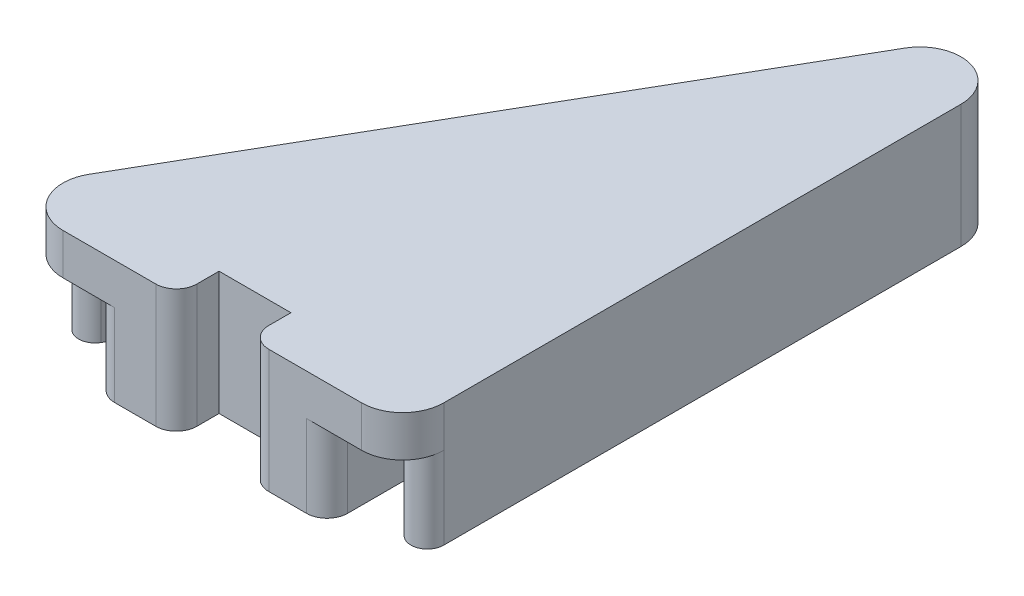
SolidWorks part; units mm, degrees
material "Pine"
ref_plane "Front Plane" through (0, 0, 0) normal (0, 0, 1) x (1, 0, 0)
ref_plane "Top Plane" through (0, 0, 0) normal (0, 1, 0) x (1, 0, 0)
ref_plane "Right Plane" through (0, 0, 0) normal (1, 0, 0) x (0, 0, -1)
sketch "Sketch1" plane through (0, 0, 0) normal (0, 1, 0) x (1, 0, 0)
  line L10 (0, 6.35) -> (0, 86.2867)
  line L11 (-11.8493, 89.4617) -> (-58.0007, 9.525)
  line L12 (-52.5015, 0) -> (-6.35, 0)
  arc A6 (-58.0007, 9.525) -> (-52.5015, 0) centre (-52.5015, 6.35) ccw
  arc A7 (0, 6.35) -> (-6.35, 0) centre (-6.35, 6.35) cw
  arc A8 (0, 86.2867) -> (-11.8493, 89.4617) centre (-6.35, 86.2867) ccw
  point P3 (-63.5, 0)
  point P4 (0, 0)
  point P7 (0, 0)
  point P10 (0, 0)
  point P13 (0, 109.9852)
  dimension "D2" = 6.35
  dimension "D1" = 63.5
  dimension "D3" = 60
extrude "Boss-Extrude1" add sketch "Sketch1" along normal blind 19.05
sketch "Sketch2" plane through (0, 19.05, 0) normal (0, 1, 0) x (1, 0, 0)
  line L0 (-52.5015, 0) -> (-6.35, 0) construction
  line L1 (-34.982, 0) -> (-23.8695, 0)
  line L2 (-34.982, 0) -> (-34.982, 6.604)
  line L3 (-34.982, 6.604) -> (-23.8695, 6.604)
  line L4 (-23.8695, 0) -> (-23.8695, 6.604)
  line L7 (0, 6.35) -> (0, 86.2867) construction
  dimension "D1" = 11.1125
  dimension "D2" = 6.604
  dimension "D3" = 23.8695
extrude "Cut-Extrude1" cut sketch "Sketch2" against normal through all
sketch "Sketch3" plane through (0, 0, 0) normal (0, 1, 0) x (1, 0, 0)
  line L0 (-22.1513, 48.2501) -> (-50.0085, 0)
  line L1 (-11.684, 45.4454) -> (-11.684, 0)
  line L2 (-11.8493, 89.4617) -> (-58.0007, 9.525) construction
  line L3 (-11.8493, 89.4617) -> (-58.0007, 9.525) construction
  line L4 (0, 86.2867) -> (0, 6.35) construction
  line L5 (0, 6.35) -> (0, 86.2867) construction
  line L7 (-5.08, 6.35) -> (-5.08, 36.8389)
  line L8 (-32.1738, 44.0986) -> (-53.6013, 6.985)
  line L9 (-41.7991, 27.427) -> (-46.1985, 29.967) construction
  line L11 (-41.7991, 27.427) -> (-36.0799, 24.125) construction
  line L12 (-5.08, 21.5944) -> (0, 21.5944) construction
  line L14 (-50.0085, 0) -> (-52.5015, 0)
  line L15 (-6.35, 0) -> (-11.684, 0)
  line L16 (-52.5015, 0) -> (-34.982, 0) construction
  line L17 (-23.8695, 0) -> (-6.35, 0) construction
  line L18 (-32.1738, 44.0986) -> (-27.8705, 51.5521)
  line L19 (-5.08, 45.4454) -> (-5.08, 36.8389)
  arc A0 (-22.1513, 48.2501) -> (-11.684, 45.4454) centre (-17.2934, 45.4454) cw
  arc A3 (-11.8493, 89.4617) -> (0, 86.2867) centre (-6.35, 86.2867) cw construction
  arc A4 (0, 86.2867) -> (-11.8493, 89.4617) centre (-6.35, 86.2867) ccw construction
  arc A7 (-5.08, 45.4454) -> (-27.8705, 51.5521) centre (-17.2934, 45.4454) ccw
  arc A10 (-53.6013, 6.985) -> (-58.0007, 9.525) centre (-55.801, 8.255) cw
  arc A11 (-58.0007, 9.525) -> (-52.5015, 0) centre (-52.5015, 6.35) ccw construction
  arc A12 (-5.08, 6.35) -> (0, 6.35) centre (-2.54, 6.35) ccw
  arc A13 (-6.35, 0) -> (0, 6.35) centre (-6.35, 6.35) ccw construction
  arc A14 (-32.1738, 44.0986) -> (-15.8416, 50.8636) centre (-19.5995, 36.8389) cw construction
  arc A15 (-15.8416, 50.8636) -> (-5.08, 36.8389) centre (-19.5995, 36.8389) cw construction
  arc A16 (-52.5015, 0) -> (-58.0007, 9.525) centre (-52.5015, 6.35) cw
  arc A17 (-6.35, 0) -> (0, 6.35) centre (-6.35, 6.35) ccw
  arc A18 (-6.35, 0) -> (0, 6.35) centre (-6.35, 6.35) ccw construction
  arc A19 (-58.0007, 9.525) -> (-52.5015, 0) centre (-52.5015, 6.35) ccw construction
  dimension "D2" = 5.08
  dimension "D3" = 316.1792
  dimension "D1" = 6.604
extrude "Cut-Extrude2" cut sketch "Sketch3" along normal blind 12.7
fillet "Fillet1" radius 3.175 4 edges at (-11.684, 6.35, 0) (-23.8695, 9.525, 0) (-34.982, 9.525, 0) (-50.0085, 6.35, 0)
ref_plane "Plane1" through (0, 0, -21.5944) normal (0, 0, 1) x (1, 0, 0)
hole_wizard "1/8 (0.125) Diameter Hole1" positions "Sketch4" profile "Sketch5" hole size "1/8" standard "ANSI Inch"
sketch "Sketch4" plane through (0, 0, 0) normal (0, -1, 0) x (-1, 0, 0)
  line L0 (34.6842, 14.224) -> (18.796, 14.224) construction
  line L1 (18.796, 14.224) -> (9.637, 74.0194) construction
  line L3 (11.684, 45.4454) -> (11.684, 3.175) construction
  line L4 (47.2588, 4.7625) -> (22.1513, 48.2501) construction
  line L5 (34.6842, 14.224) -> (41.7962, 14.224) construction
  line L7 (4.7065, 92.4203) -> (9.637, 74.0194) construction
  line L8 (13.9069, 94.8856) -> (-4.4939, 89.9551) construction
  arc A0 (11.8493, 89.4617) -> (0, 86.2867) centre (6.35, 86.2867) ccw construction
  point P0 (9.637, 74.0194)
  point P2 (18.796, 14.224)
  point P4 (34.6842, 14.224)
  point P33 (4.7065, 92.4203)
  dimension "D1" = 14.224
  dimension "D2" = 7.112
  dimension "D3" = 7.112
  dimension "D4" = 19.05
sketch "Sketch5" plane through (-9.637, 0, -74.0194) normal (1, 0, 0) x (0, 0, -1)
  line L0 (0, 0) -> (0, 12.0791)
  line L1 (0, 12.0791) -> (1.5875, 11.1252)
  line L2 (1.5875, 11.1252) -> (1.5875, 0)
  line L5 (1.5875, 0) -> (0, 0)
  line L10 (0, 12.0791) -> (-1.5875, 11.1252) construction
  line L11 (0, -6.35) -> (0, 107.95) construction
  dimension "Hole Dia." = 3.175
  dimension "Hole Depth" = 11.1252
  dimension "Drill Angle" = 118
